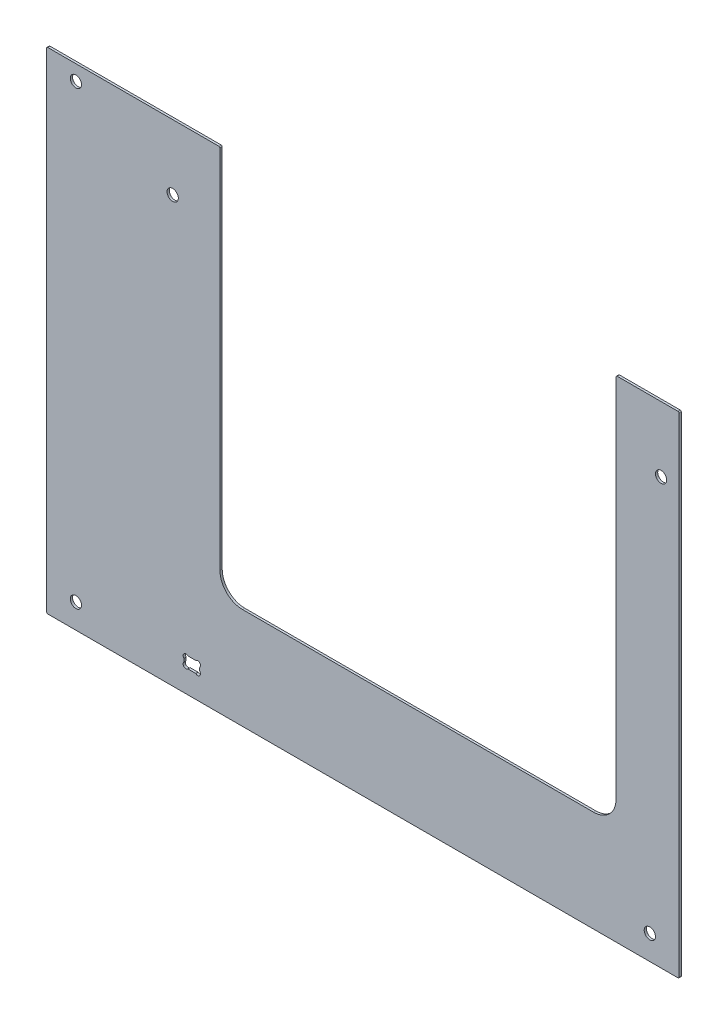
SolidWorks part; units mm, degrees
ref_plane "Front Plane" through (0, 0, 0) normal (0, 0, 1) x (1, 0, 0)
ref_plane "Top Plane" through (0, 0, 0) normal (0, 1, 0) x (1, 0, 0)
ref_plane "Right Plane" through (0, 0, 0) normal (1, 0, 0) x (0, 0, -1)
sketch "Sketch1" plane through (0, 0, 0) normal (0, 0, 1) x (1, 0, 0)
  line L0 (77, 218) -> (77, 55)
  line L1 (0, 0) -> (281, 0)
  line L5 (87, 45) -> (243, 45)
  line L6 (0, 0) -> (0, 218)
  line L8 (0, 218) -> (77, 218)
  line L9 (281, 0) -> (281, 218)
  line L10 (281, 218) -> (253, 218)
  line L13 (61, 15) -> (68, 15)
  line L14 (61, 15) -> (61, 10)
  line L15 (253, 55) -> (253, 218)
  line L16 (61, 10) -> (68, 10)
  line L17 (68, 15) -> (68, 10)
  line L38 (283, 135) -> (253, 135) construction
  line L39 (47, 135) -> (77, 135) construction
  circle A0 centre (13, 10.85) radius 1.65 construction
  circle A1 centre (13, 10.85) radius 2.5
  circle A2 centre (13, 211.15) radius 2.5
  circle A3 centre (13, 211.15) radius 1.65 construction
  circle A4 centre (56, 189) radius 2.5
  circle A5 centre (268, 10.85) radius 1.65 construction
  circle A6 centre (268, 10.85) radius 2.5
  circle A7 centre (273, 189) radius 2.5
  arc A8 (243, 45) -> (253, 55) centre (243, 55) ccw
  arc A9 (87, 45) -> (77, 55) centre (87, 55) cw
  point P2 (253, 45)
  point P8 (77, 45)
  dimension "D9" = 15
  dimension "D7" = 21
  dimension "D22" = 5
  dimension "D10" = 173
  dimension "D14" = 3.3
  dimension "D18" = 5
  dimension "D3" = 10
  dimension "D4" = 281
  dimension "D6" = 176
  dimension "D8" = 200.3
  dimension "D12" = 45
  dimension "D13" = 7
  dimension "D15" = 9
  dimension "D16" = 64
  dimension "D17" = 20
  dimension "D19" = 34.15
  dimension "D21" = 144
  dimension "D23" = 30
  dimension "D24" = 77
  dimension "D25" = 28
  dimension "D26" = 178.15
extrude "1mm Stainless_Steal" add sketch "Sketch1" along normal blind 1
sketch "Sketch3" plane through (0, 0, 1) normal (0, 0, 1) x (1, 0, 0)
  line L0 (61, 10.8839) -> (61.8839, 10.8839) construction
  line L2 (61, 15) -> (61, 10) construction
  line L4 (61, 10) -> (68, 10) construction
  line L5 (64.5, 10) -> (64.5, 12.5) construction
  line L6 (64.5, 12.5) -> (61, 12.5) construction
  line L7 (61.8839, 10.8839) -> (61.8839, 10) construction
  circle A0 centre (61.8839, 14.1161) radius 1.25
  circle A1 centre (67.1161, 10.8839) radius 1.25
  circle A2 centre (67.1161, 14.1161) radius 1.25
  circle A4 centre (61.8839, 10.8839) radius 1.25
  dimension "D1" = 2.5
extrude "Cut-Extrude2" cut sketch "Sketch3" against normal through all
fillet "Fillet2_1mm_Stainless_Steal" radius 0.5 6 edges at (281, 218, 0.5) (253, 218, 0.5) (0, 218, 0.5) (77, 218, 0.5) (0, 0, 0.5) (281, 0, 0.5)
